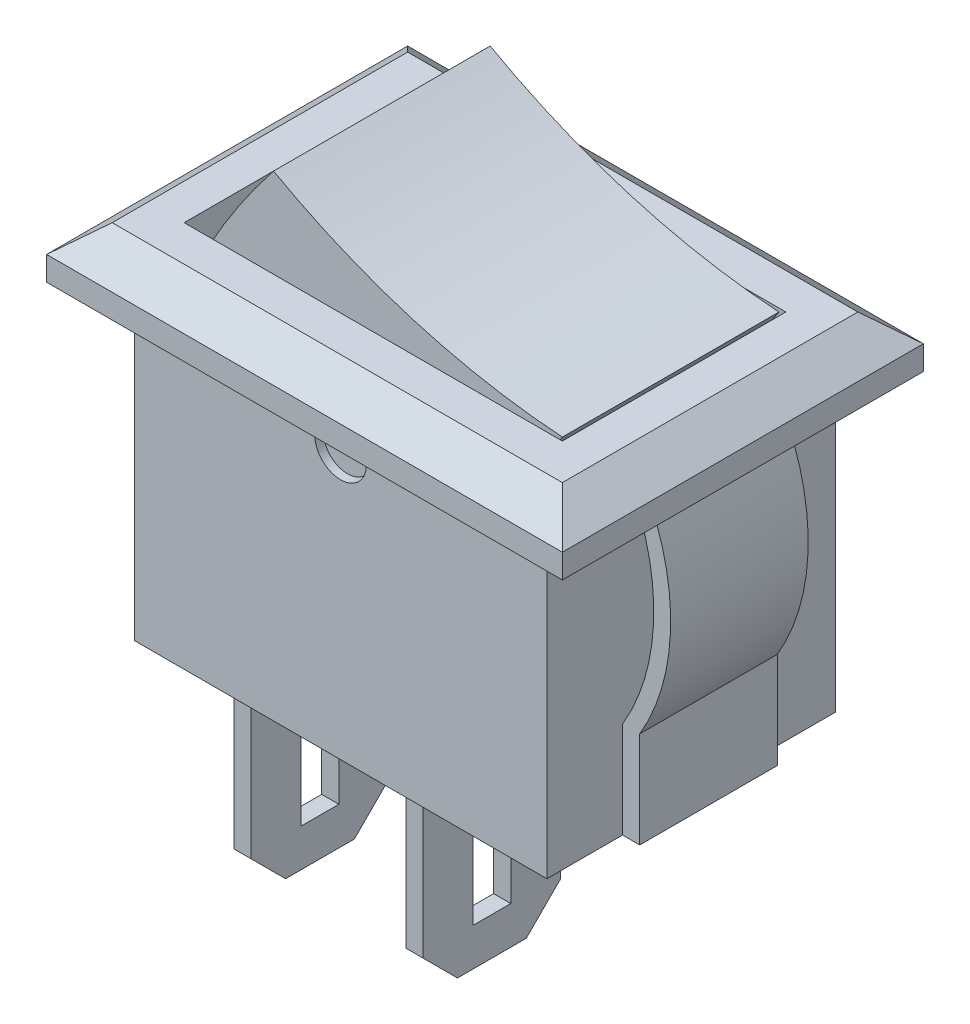
SolidWorks part; units mm, degrees
ref_plane "Alzado" through (0, 0, 0) normal (0, 0, 1) x (1, 0, 0)
ref_plane "Planta" through (0, 0, 0) normal (0, 1, 0) x (1, 0, 0)
ref_plane "Vista lateral" through (0, 0, 0) normal (1, 0, 0) x (0, 0, -1)
sketch "Croquis1" plane through (0, 0, 0) normal (0, 1, 0) x (1, 0, 0)
  line L1 (-6, -4.2) -> (6, -4.2)
  line L2 (-6, -4.2) -> (-6, 4.2)
  line L3 (-6, 4.2) -> (6, 4.2)
  line L4 (6, -4.2) -> (6, 4.2)
  line L5 (-6, -4.2) -> (6, 4.2) construction
  line L6 (-6, 4.2) -> (6, -4.2) construction
  point P0 (0, 0)
  dimension "D1" = 12
  dimension "D2" = 8.4
extrude "Saliente-Extruir1" add sketch "Croquis1" along normal blind 8.8
sketch "Croquis2" plane through (0, 8.8, 0) normal (0, 1, 0) x (1, 0, 0)
  line L1 (-7.5, -5.25) -> (7.5, -5.25)
  line L2 (-7.5, -5.25) -> (-7.5, 5.25)
  line L3 (-7.5, 5.25) -> (7.5, 5.25)
  line L4 (7.5, -5.25) -> (7.5, 5.25)
  line L5 (-7.5, -5.25) -> (7.5, 5.25) construction
  line L6 (-7.5, 5.25) -> (7.5, -5.25) construction
  point P0 (0, 0)
  dimension "D1" = 10.5
  dimension "D2" = 15
extrude "Saliente-Extruir2" add sketch "Croquis2" along normal blind 0.7
sketch "Croquis3" plane through (0, 9.5, 0) normal (0, 1, 0) x (1, 0, 0)
  line L4 (7.5, -5.25) -> (7.5, 5.25)
  line L5 (7.5, 5.25) -> (-7.5, 5.25)
  line L6 (-7.5, 5.25) -> (-7.5, -5.25)
  line L7 (-7.5, -5.25) -> (7.5, -5.25)
  line L8 (7.5, -5.25) -> (7.5, 5.25)
  line L9 (7.5, 5.25) -> (-7.5, 5.25)
  line L10 (-7.5, 5.25) -> (-7.5, -5.25)
  line L11 (-7.5, -5.25) -> (7.5, -5.25)
  dimension "D1" = 0
extrude "Saliente-Extruir3" add sketch "Croquis3" along normal blind 0.8 draft 50
sketch "Croquis6" plane through (0, 0, 0) normal (0, 0, 1) x (1, 0, 0)
  line L0 (0, 8.8) -> (0, 0) construction
  line L1 (-6, 8.8) -> (6, 8.8) construction
  line L2 (-7.5, 8.8) -> (7.5, 8.8) construction
  circle A0 centre (0, 7.8) radius 0.75
  dimension "D1" = 1.5
  dimension "D2" = 1
sketch "Croquis4" plane through (0, 10.3, 0) normal (0, 1, 0) x (1, 0, 0)
  line L1 (-5.5, -3.25) -> (5.5, -3.25)
  line L2 (-5.5, -3.25) -> (-5.5, 3.25)
  line L3 (-5.5, 3.25) -> (5.5, 3.25)
  line L4 (5.5, -3.25) -> (5.5, 3.25)
  line L5 (-5.5, -3.25) -> (5.5, 3.25) construction
  line L6 (-5.5, 3.25) -> (5.5, -3.25) construction
  point P0 (0, 0)
  dimension "D1" = 11
  dimension "D2" = 6.5
extrude "Cortar-Extruir1" cut sketch "Croquis4" against normal blind 9
extrude "Cortar-Extruir7" cut sketch "Croquis6" against normal through all both and the other way through all
sketch "Croquis5" plane through (0, 0, 0) normal (0, 0, 1) x (1, 0, 0)
  line L0 (5.4, 4.2389) -> (5.4, 13.5486) construction
  line L1 (5.5, 1.3) -> (5.5, 10.3) construction
  line L2 (-6.5466, 10.3) -> (6.5466, 10.3) construction
  line L3 (5.4, 10.3) -> (6.5466, 10.3) construction
  line L4 (-4.7, 12.0605) -> (-4.7, 6.3501) construction
  line L5 (-6.5466, 10.3) -> (-4.7, 10.3) construction
  line L6 (5.4, 10.3) -> (6.5466, 10.3) construction
  line L7 (-3, 10.3) -> (-3, 12.8) construction
  line L8 (-7.5, 9.5) -> (-7.5, 8.8) construction
  line L9 (-7.5, 8.8) -> (7.5, 8.8) construction
  line L10 (-7.5, 9.5) -> (7.5, 9.5) construction
  line L11 (-5.3, 12.0605) -> (-5.3, 9.1741) construction
  arc A0 (-3, 12.8) -> (5.4, 10.3) centre (6.7664, 30.2533) ccw
  arc A1 (-3, 12.8) -> (-5.3, 9.1741) centre (12.6412, 0.336) ccw
  circle A2 centre (0, 7.8) radius 0.75 construction
  arc A3 (-5.3, 9.1741) -> (5.4, 10.3) centre (-0.3757, 13.7827) ccw
  point P24 (0, 9.5)
  dimension "D1" = 40
  dimension "D3" = 40
  dimension "D7" = 1.5
  dimension "D2" = 0.1
  dimension "D4" = 0.8
  dimension "D5" = 2.5
  dimension "D6" = 4.5
  dimension "D8" = 1
  dimension "D9" = 0.2
extrude "Saliente-Extruir4" add sketch "Croquis5" along normal mid plane 6.3 separate body
sketch "Croquis7" plane through (0, 0, 0) normal (0, 0, 1) x (1, 0, 0)
  circle A0 centre (0, 7.8) radius 0.7
  dimension "D1" = 1.4
extrude "Saliente-Extruir5" add sketch "Croquis7" along normal mid plane 8
sketch "Croquis8" plane through (0, 0, 0) normal (0, 0, 1) x (1, 0, 0)
  line L0 (0, 8.8) -> (0, 0) construction
  line L1 (-6, 8.8) -> (6, 8.8) construction
  line L2 (-6, 0) -> (6, 0) construction
  line L3 (-6.5, 0) -> (-6.5, 2.8)
  line L4 (-6.5, 0) -> (-6, 0)
  line L6 (-6, 8.8) -> (-6, 0) construction
  line L7 (-6.3042, 8.8) -> (-6.8, 8.8)
  line L8 (-7.5, 8.8) -> (7.5, 8.8) construction
  line L9 (-0.956, 6.0847) -> (-7.4, 6.0847) construction
  line L11 (-6, 0) -> (-6, 2.8)
  line L12 (6.5, 0) -> (6, 0)
  line L13 (6.5, 0) -> (6.5, 2.8)
  line L14 (6.3042, 8.8) -> (6.8, 8.8)
  line L15 (6, 0) -> (6, 2.8)
  arc A0 (-6.8, 8.8) -> (-6.5, 2.8) centre (-0.956, 6.0847) ccw
  arc A1 (-6.3042, 8.8) -> (-6, 2.8) centre (-0.5094, 6.086) ccw
  arc A2 (6.8, 8.8) -> (6.5, 2.8) centre (0.956, 6.0847) cw
  arc A3 (6.3042, 8.8) -> (6, 2.8) centre (0.5094, 6.086) cw
  point P19 (-6.9, 5.7621)
  dimension "D1" = 6.5
  dimension "D2" = 6.8
  dimension "D3" = 7.4
  dimension "D4" = 2.8
  dimension "D5" = 0.4958
  dimension "D6" = 0.5
extrude "Saliente-Extruir6" add sketch "Croquis8" along normal mid plane 4
sketch "Croquis9" plane through (0, 0, 0) normal (0, -1, 0) x (1, 0, 0)
  line L0 (-6.5, 0) -> (6.5, 0) construction
  line L1 (-5.3, -2) -> (-4.8, -2)
  line L2 (-5.3, -2) -> (-5.3, 2)
  line L3 (-5.3, 2) -> (-4.8, 2)
  line L4 (-4.8, -2) -> (-4.8, 2)
  line L5 (-5.3, -2) -> (-4.8, 2) construction
  line L6 (-5.3, 2) -> (-4.8, -2) construction
  line L7 (-6.5, 2) -> (-6.5, -2) construction
  line L8 (6.5, 2) -> (6.5, -2) construction
  line L9 (-0.3, -2) -> (-0.3, 2)
  line L10 (-0.3, -2) -> (0.2, -2)
  line L11 (0.2, -2) -> (0.2, 2)
  line L12 (-0.3, 2) -> (0.2, 2)
  point P0 (-5.05, 0)
  dimension "D1" = 4
  dimension "D2" = 0.5
  dimension "D3" = 1.2
  dimension "D5" = 4.5
  dimension "D4" = 2
extrude "Saliente-Extruir7" add sketch "Croquis9" along normal blind 7 separate body
sketch "Croquis10" plane through (-5.3, 0, 0) normal (-1, 0, 0) x (0, 0, 1)
  line L0 (2, -7) -> (-2, -7) construction
  line L1 (-0.55, -3.3) -> (0.55, -3.3)
  line L2 (-0.55, -3.3) -> (-0.55, -5.9)
  line L3 (-0.55, -5.9) -> (0.55, -5.9)
  line L4 (0.55, -3.3) -> (0.55, -5.9)
  line L5 (-0.55, -3.3) -> (0.55, -5.9) construction
  line L6 (-0.55, -5.9) -> (0.55, -3.3) construction
  line L7 (-2, -6) -> (-1, -7)
  line L8 (-2, -7) -> (-2, 0) construction
  line L9 (-1, -7) -> (-2, -7)
  line L10 (-2, -7) -> (-2, -6)
  line L11 (2, -6) -> (1, -7)
  line L12 (2, -7) -> (2, 0) construction
  line L13 (1, -7) -> (2, -7)
  line L14 (2, -7) -> (2, -6)
  point P0 (0, -4.6)
  dimension "D1" = 1.1
  dimension "D2" = 2.6
  dimension "D3" = 1.1
  dimension "D4" = 45
  dimension "D5" = 1
extrude "Cortar-Extruir8" cut sketch "Croquis10" against normal through all both
